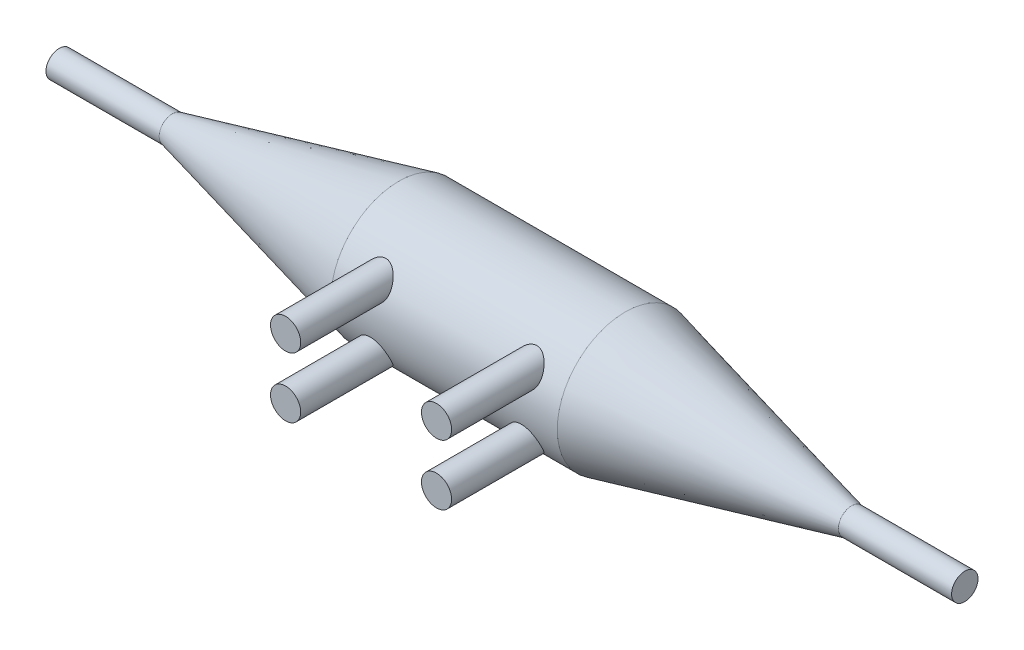
SolidWorks part; units mm, degrees
ref_plane "Front Plane" through (0, 0, 0) normal (0, 0, 1) x (1, 0, 0)
ref_plane "Top Plane" through (0, 0, 0) normal (0, 1, 0) x (1, 0, 0)
ref_plane "Right Plane" through (0, 0, 0) normal (1, 0, 0) x (0, 0, -1)
sketch "Sketch1" plane through (0, 0, 0) normal (0, 0, 1) x (1, 0, 0)
  line L0 (-16.7408, 1.75) -> (-1.7408, 1.75)
  line L1 (-1.7408, 1.75) -> (28.2592, 9)
  line L2 (28.2592, 9) -> (58.2592, 9)
  line L3 (58.2592, 9) -> (88.2592, 1.75)
  line L4 (88.2592, 1.75) -> (103.2592, 1.75)
  line L5 (103.2592, 1.75) -> (103.2592, 0)
  line L6 (103.2592, 0) -> (-16.7408, 0)
  line L7 (-16.7408, 0) -> (-16.7408, 1.75)
  dimension "D1" = 1.75
  dimension "D2" = 9
  dimension "D3" = 30
  dimension "D4" = 120
  dimension "D5" = 30
  dimension "D6" = 15
  dimension "D7" = 15
revolve "Revolve1" add sketch "Sketch1" angle 360 about L6
sketch "Sketch2" plane through (0, 0, 0) normal (0, 0, 1) x (1, 0, 0)
  line L0 (21.8042, 4) -> (64.597, 4) construction
  line L1 (21.8042, -4) -> (64.597, -4) construction
  line L2 (58.2592, 9) -> (28.2592, 9) construction
  line L3 (33.2592, 4) -> (33.2592, -4) construction
  line L4 (28.2592, 9) -> (28.2592, -9) construction
  circle A0 centre (33.2592, 4) radius 2
  circle A1 centre (33.2592, -4) radius 2
  circle A2 centre (53.2592, 4) radius 2
  circle A3 centre (53.2592, -4) radius 2
  dimension "D5" = 5
  dimension "D1" = 8
  dimension "D2" = 5
  dimension "D3" = 20
  dimension "D4" = 20
extrude "Boss-Extrude1" add sketch "Sketch2" along normal blind 20
